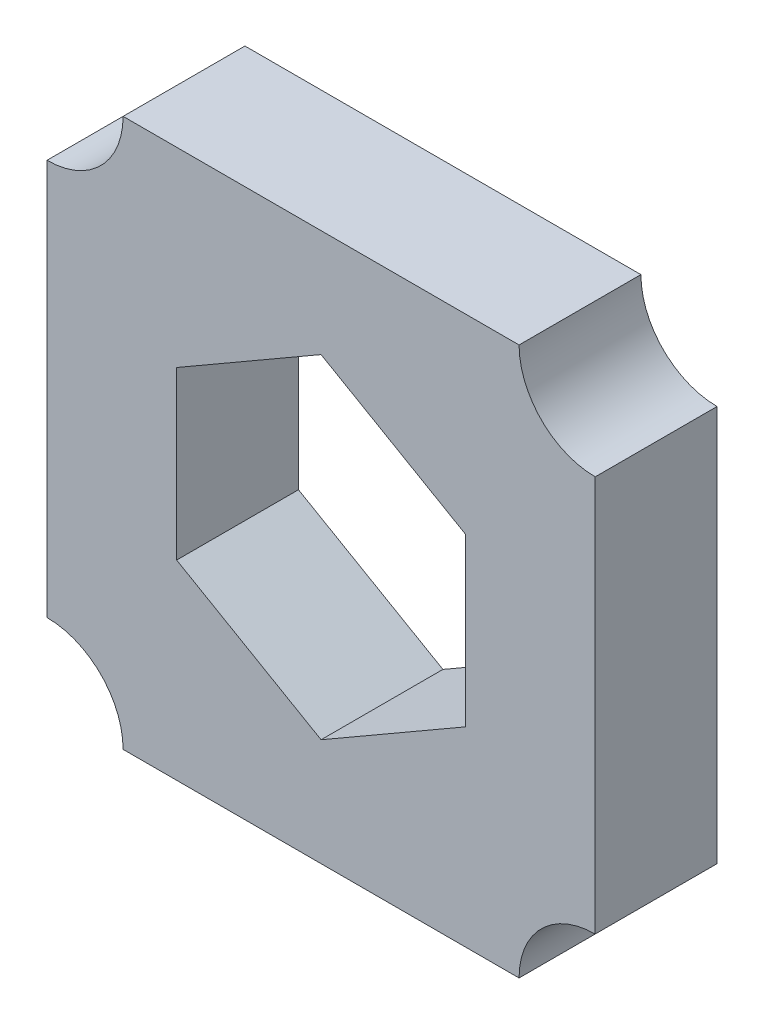
SolidWorks part; units mm, degrees
ref_plane "Front Plane" through (0, 0, 0) normal (0, 0, 1) x (1, 0, 0)
ref_plane "Top Plane" through (0, 0, 0) normal (0, 1, 0) x (1, 0, 0)
ref_plane "Right Plane" through (0, 0, 0) normal (1, 0, 0) x (0, 0, -1)
sketch "Sketch1" plane through (0, 0, 0) normal (0, 0, 1) x (1, 0, 0)
  line L0 (45, 90) -> (45, 0) construction
  line L1 (12.5, 0) -> (77.5, 0)
  line L2 (0, 12.5) -> (0, 77.5)
  line L3 (12.5, 90) -> (77.5, 90)
  line L4 (90, 12.5) -> (90, 77.5)
  line L5 (0, 45) -> (109.0588, 45) construction
  line L7 (45, 72.3782) -> (21.2898, 58.6891)
  line L8 (21.2898, 58.6891) -> (21.2898, 31.3109)
  line L9 (21.2898, 31.3109) -> (45, 17.6218)
  line L10 (45, 17.6218) -> (68.7102, 31.3109)
  line L11 (68.7102, 31.3109) -> (68.7102, 58.6891)
  line L12 (68.7102, 58.6891) -> (45, 72.3782)
  circle A0 centre (45, 45) radius 23.7102 construction
  arc A1 (12.5, 0) -> (0, 12.5) centre (0, 0) ccw
  arc A2 (0, 77.5) -> (12.5, 90) centre (0, 90) ccw
  arc A3 (77.5, 90) -> (90, 77.5) centre (90, 90) ccw
  arc A4 (90, 12.5) -> (77.5, 0) centre (90, 0) ccw
  point P22 (0, 0)
  point P26 (0, 0)
  point P27 (0, 0)
  point P28 (0, 0)
  point P29 (0, 0)
  point P30 (0, 0)
  point P31 (0, 0)
  dimension "D3" = 25
  dimension "D4" = 25
  dimension "D5" = 25
  dimension "D6" = 25
  dimension "D1" = 90
  dimension "D2" = 90
  dimension "D7" = 45
extrude "Boss-Extrude3" add sketch "Sketch1" along normal mid plane 20
